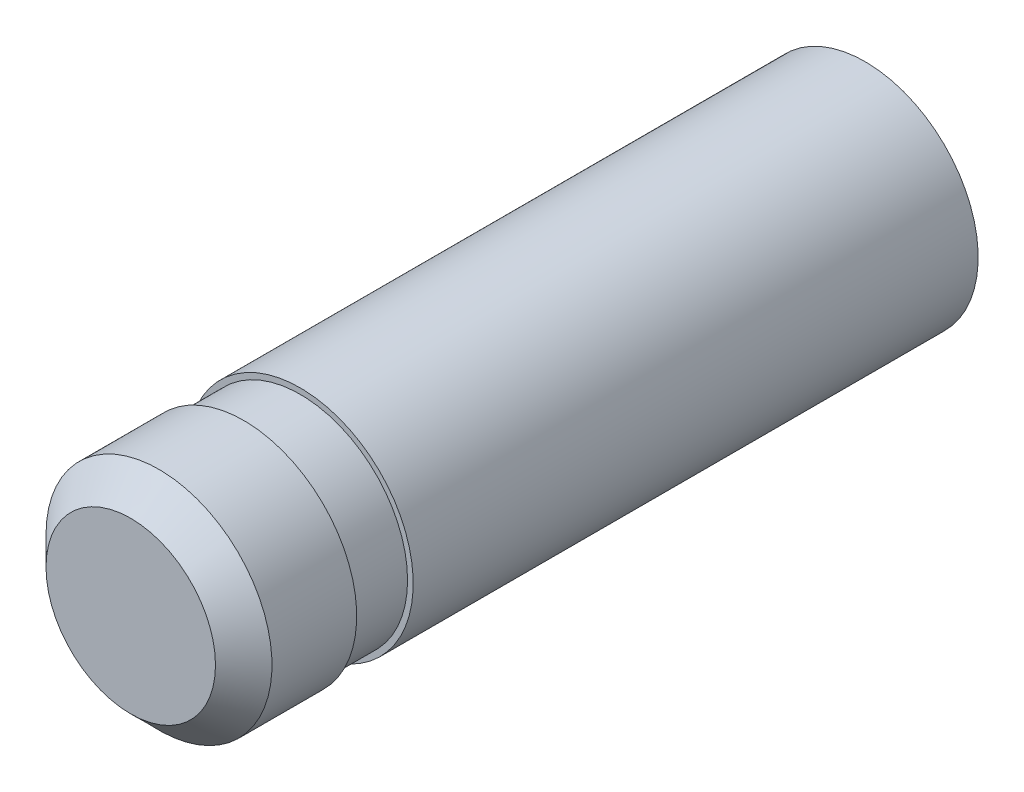
SolidWorks part; units mm, degrees
material "1023 Carbon Steel Sheet (SS)"
ref_plane "Front Plane" through (0, 0, 0) normal (0, 0, 1) x (1, 0, 0)
ref_plane "Top Plane" through (0, 0, 0) normal (0, 1, 0) x (1, 0, 0)
ref_plane "Right Plane" through (0, 0, 0) normal (1, 0, 0) x (0, 0, -1)
sketch "Sketch1" plane through (0, 0, 0) normal (0, 0, 1) x (1, 0, 0)
  circle A0 centre (0, 0) radius 2
  dimension "D1" = 4
extrude "Boss-Extrude1" add sketch "Sketch1" along normal blind 13
sketch "Sketch2" plane through (0, 0, 0) normal (0, 0, -1) x (-1, 0, 0)
  circle A0 centre (0, 0) radius 1.9
  dimension "D1" = 3.8
extrude "Cut-Extrude1" cut sketch "Sketch2" against normal blind 1 from offset 10 flip side to cut offset against normal yes
chamfer "Chamfer1" distance 0.5 angle 45 1 edges at (2, 0, 13)
